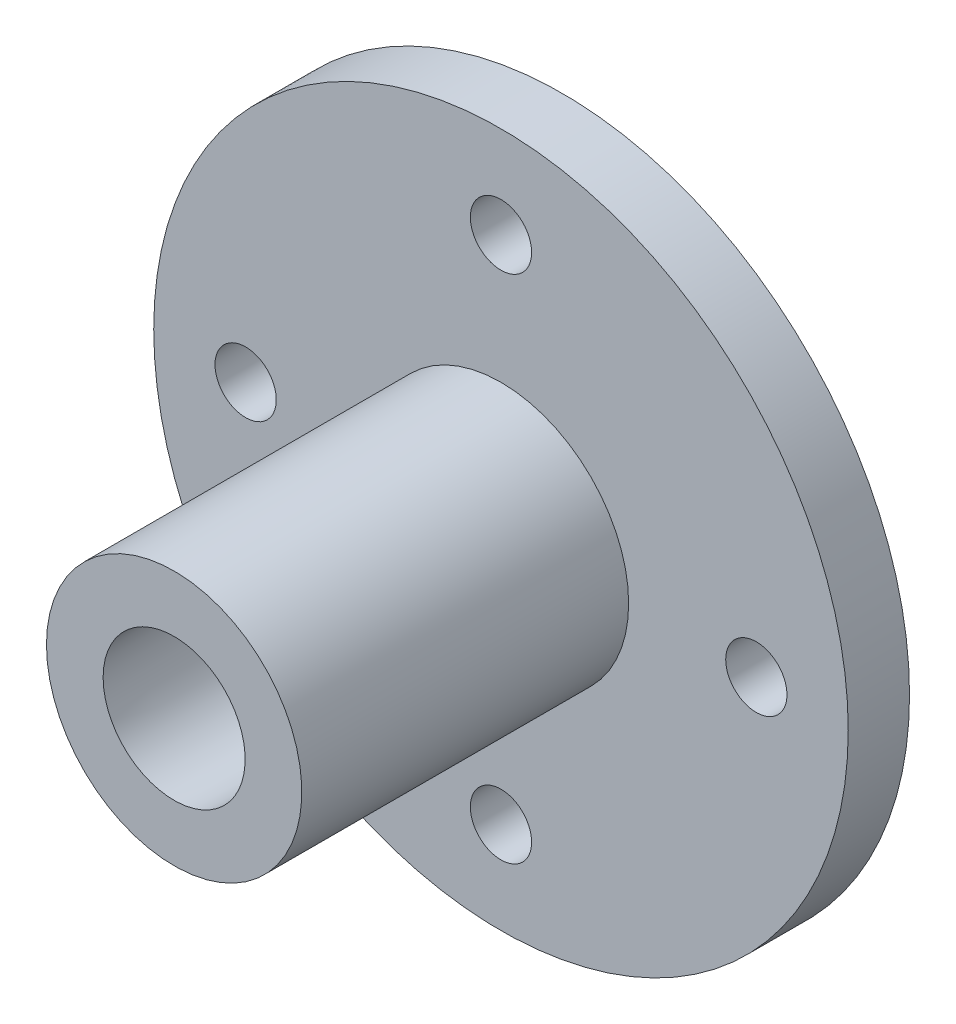
SolidWorks part; units mm, degrees
ref_plane "Front Plane" through (0, 0, 0) normal (0, 0, 1) x (1, 0, 0)
ref_plane "Top Plane" through (0, 0, 0) normal (0, 1, 0) x (1, 0, 0)
ref_plane "Right Plane" through (0, 0, 0) normal (1, 0, 0) x (0, 0, -1)
sketch "Sketch1" plane through (0, 0, 0) normal (0, 0, 1) x (1, 0, 0)
  circle A0 centre (0, 0) radius 17
  dimension "D1" = 34
extrude "Boss-Extrude1" add sketch "Sketch1" along normal blind 3
sketch "Sketch2" plane through (0, 0, 0) normal (0, 0, -1) x (-1, 0, 0)
  circle A0 centre (0, 0) radius 12.5 construction
  circle A1 centre (0, 12.5) radius 1.5
  circle A2 centre (12.5, 0) radius 1.5
  circle A3 centre (0, -12.5) radius 1.5
  circle A4 centre (-12.5, 0) radius 1.5
  circle A5 centre (0, 0) radius 17 construction
  point P14 (0, 0)
  dimension "D1" = 25
  dimension "D2" = 3
  dimension "D3" = 4
extrude "Cut-Extrude1" cut sketch "Sketch2" against normal through all
sketch "Sketch3" plane through (0, 0, 0) normal (0, 0, -1) x (-1, 0, 0)
  circle A0 centre (0, 0) radius 6.25
  dimension "D1" = 12.5
extrude "Boss-Extrude2" add sketch "Sketch3" along normal blind 1
sketch "Sketch5" plane through (0, 0, -1) normal (0, 0, -1) x (-1, 0, 0)
  circle A1 centre (0, 0) radius 6.25
  circle A2 centre (0, 0) radius 6.25
  dimension "D1" = 0
extrude "Boss-Extrude3" add sketch "Sketch5" against normal blind 20
sketch "Sketch6" plane through (0, 0, -1) normal (0, 0, -1) x (-1, 0, 0)
  circle A0 centre (0, 0) radius 4
  dimension "D1" = 8
extrude "Cut-Extrude2" cut sketch "Sketch6" against normal through all draft 1.5
sketch "Sketch7" plane through (0, 0, 0) normal (0, 0, -1) x (-1, 0, 0)
  circle A0 centre (0, 12.5) radius 1.85
  circle A1 centre (0, 12.5) radius 1.5 construction
  circle A2 centre (12.5, 0) radius 1.85
  circle A3 centre (0, -12.5) radius 1.85
  circle A4 centre (-12.5, 0) radius 1.85
  circle A5 centre (-12.5, 0) radius 1.5 construction
  circle A6 centre (0, -12.5) radius 1.5 construction
  circle A7 centre (12.5, 0) radius 1.5 construction
  circle A8 centre (0, -12.5) radius 1.5
  circle A9 centre (12.5, 0) radius 1.5
  circle A10 centre (-12.5, 0) radius 1.5
  circle A11 centre (0, 12.5) radius 1.5
  dimension "D1" = 0.35
extrude "Cut-Extrude3" cut sketch "Sketch7" against normal blind 0.25
